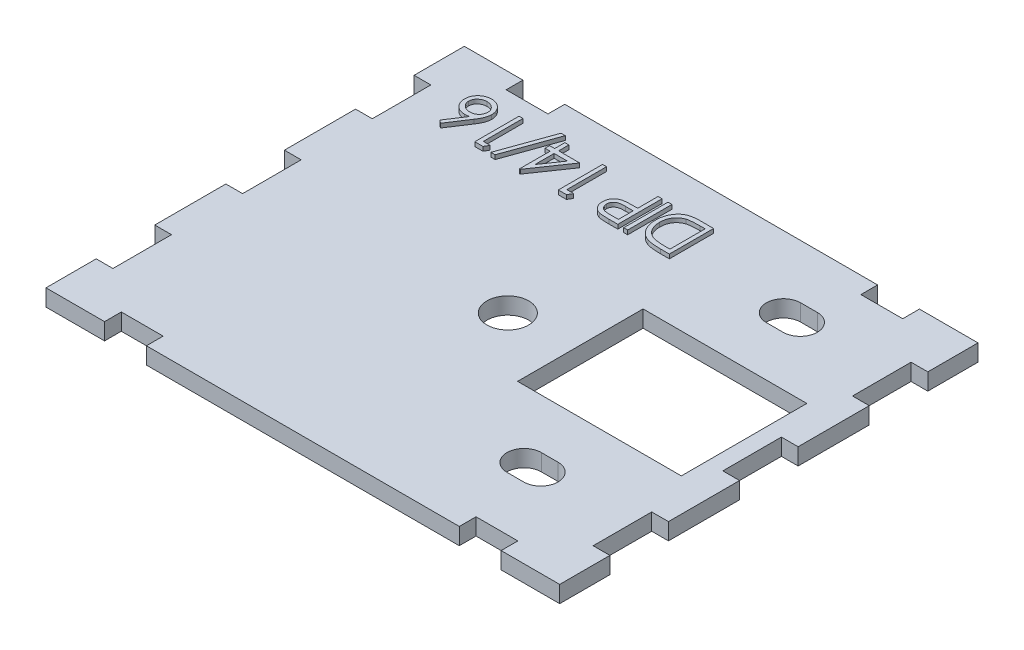
SolidWorks part; units mm, degrees
ref_plane "Front Plane" through (0, 0, 0) normal (0, 0, 1) x (1, 0, 0)
ref_plane "Top Plane" through (0, 0, 0) normal (0, 1, 0) x (1, 0, 0)
ref_plane "Right Plane" through (0, 0, 0) normal (1, 0, 0) x (0, 0, -1)
sketch "Sketch2" plane through (0, 0, 0) normal (0, 1, 0) x (1, 0, 0)
  line L1 (-50, 25) -> (50, 25)
  line L2 (-50, 25) -> (-50, -25)
  line L3 (-50, -25) -> (50, -25)
  line L4 (50, 25) -> (50, -25)
  line L5 (-50, 25) -> (50, -25) construction
  line L6 (-50, -25) -> (50, 25) construction
  point P0 (0, 0)
  dimension "D1" = 100
  dimension "D2" = 50
extrude "Boss-Extrude1" add sketch "Sketch2" along normal blind 2
sketch "Sketch12" plane through (0, 2, 0) normal (0, 1, 0) x (1, 0, 0)
  line L0 (-50, -25) -> (50, -25) construction
  line L1 (-40.2, -25) -> (-50, -25)
  line L2 (-40.2, -25) -> (-40.2, 25)
  line L3 (-40.2, 25) -> (-50, 25)
  line L4 (-50, -25) -> (-50, 25)
  line L5 (-50, -25) -> (50, -25) construction
  line L6 (41.2, -25) -> (50, -25)
  line L7 (41.2, -25) -> (41.2, 25)
  line L8 (41.2, 25) -> (50, 25)
  line L9 (50, -25) -> (50, 25)
extrude "Cut-Extrude8" cut sketch "Sketch12" against normal blind 6
sketch "Sketch13" plane through (0, 2, 0) normal (0, 1, 0) x (1, 0, 0)
  line L1 (-28.2, 19) -> (-30.2, 19)
  line L2 (-28.2, 19) -> (-28.2, 12)
  line L3 (-28.2, 12) -> (-30.2, 12)
  line L4 (-30.2, 19) -> (-30.2, 12)
  line L5 (-28.2, 3.5) -> (-30.2, 3.5)
  line L6 (-28.2, 3.5) -> (-28.2, -3.5)
  line L7 (-28.2, -3.5) -> (-30.2, -3.5)
  line L8 (-30.2, 3.5) -> (-30.2, -3.5)
  line L9 (-28.2, -12) -> (-30.2, -12)
  line L10 (-28.2, -12) -> (-28.2, -19)
  line L11 (-28.2, -19) -> (-30.2, -19)
  line L12 (-30.2, -12) -> (-30.2, -19)
  line L13 (29.2, 19) -> (31.2, 19)
  line L14 (29.2, 19) -> (29.2, 12)
  line L15 (29.2, 12) -> (31.2, 12)
  line L16 (31.2, 19) -> (31.2, 12)
  line L17 (29.2, 3.5) -> (31.2, 3.5)
  line L18 (29.2, 3.5) -> (29.2, -3.5)
  line L19 (29.2, -3.5) -> (31.2, -3.5)
  line L20 (31.2, 3.5) -> (31.2, -3.5)
  line L21 (29.2, -12) -> (31.2, -12)
  line L22 (29.2, -12) -> (29.2, -19)
  line L23 (29.2, -19) -> (31.2, -19)
  line L24 (31.2, -12) -> (31.2, -19)
  line L25 (-40.2, -25) -> (41.2, -25) construction
  line L26 (-23.2, 25) -> (-18.2, 25)
  line L27 (41.2, 25) -> (-40.2, 25) construction
  line L28 (-40.2, -25) -> (41.2, -25) construction
  line L29 (41.2, 25) -> (-40.2, 25) construction
  line L30 (-40.2, -25) -> (41.2, -25) construction
  line L31 (41.2, 25) -> (31.2, 25)
  line L32 (41.2, 25) -> (41.2, -25)
  line L33 (41.2, -25) -> (31.2, -25)
  line L34 (31.2, 25) -> (31.2, -25)
  line L35 (41.2, 25) -> (-40.2, 25) construction
  line L36 (-40.2, -25) -> (-30.2, -25)
  line L37 (-40.2, -25) -> (-40.2, 25)
  line L38 (-40.2, 25) -> (-30.2, 25)
  line L39 (-30.2, -25) -> (-30.2, 25)
  line L40 (-23.2, 25) -> (-23.2, 23)
  line L41 (-23.2, 23) -> (-18.2, 23)
  line L42 (-18.2, 25) -> (-18.2, 23)
  line L43 (-23.2, -25) -> (-18.2, -25)
  line L44 (-23.2, -25) -> (-23.2, -23)
  line L45 (-23.2, -23) -> (-18.2, -23)
  line L46 (-18.2, -25) -> (-18.2, -23)
  line L47 (24.2, -25) -> (19.2, -25)
  line L48 (24.2, -25) -> (24.2, -23)
  line L49 (24.2, -23) -> (19.2, -23)
  line L50 (19.2, -25) -> (19.2, -23)
  line L51 (24.2, 25) -> (19.2, 25)
  line L52 (24.2, 25) -> (24.2, 23)
  line L53 (24.2, 23) -> (19.2, 23)
  line L54 (19.2, 25) -> (19.2, 23)
  point P24 (29.2, 0)
  point P30 (30.2, 3.5)
  line M32 (41.2, -25) -> (41.2, 25)
  line M41 (41.2, 25) -> (-40.2, 25)
  line M42 (-40.2, 25) -> (-40.2, -25)
  line M47 (-40.2, -25) -> (41.2, -25)
  dimension "D1" = 2
  dimension "D2" = 2
  dimension "D3" = 2
  dimension "D4" = 2
  dimension "D5" = 2
  dimension "D6" = 2
  dimension "D7" = 57.4
  dimension "D8" = 57.4
  dimension "D9" = 57.4
  dimension "D10" = 7
  dimension "D11" = 7
  dimension "D12" = 7
  dimension "D13" = 7
  dimension "D14" = 7
  dimension "D15" = 7
  dimension "D16" = 5
  dimension "D17" = 2
  dimension "D18" = 5
  dimension "D19" = 6
  dimension "D20" = 8.5
  dimension "D21" = 8.5
  dimension "D22" = 6
  dimension "D23" = 6
  dimension "D24" = 8.5
  dimension "D25" = 8.5
  dimension "D26" = 6
  dimension "D27" = 5
  dimension "D28" = 5
  dimension "D29" = 2
  dimension "D30" = 2
  dimension "D31" = 5
  dimension "D32" = 5
  dimension "D33" = 5
  dimension "D34" = 5
  dimension "D35" = 2
extrude "Cut-Extrude10" cut sketch "Sketch13" against normal blind 6 contours L5 L8 L7 L6 | L39 L12 L8 L4 M47 M41 M42 | L1 L4 L3 L2 | L50 L48 L49 M47 | L24 L21 L22 L23 | L20 L17 L18 L19 | L16 L13 L14 L15 | L54 L53 L52 M41 | L9 L12 L11 L10 | L34 L16 L20 L24 M41 M47 M32 | L26 L42 L41 L40 | L45 L46 L43 L44
sketch "Sketch15" plane through (0, 0, 0) normal (0, -1, 0) x (1, 0, 0)
  line L0 (24.2, 23) -> (19.2, 23) construction
  line L1 (31.2, -12) -> (31.2, -3.5) construction
  line L16 (20.7242, -7.5) -> (20.7242, -8.5)
  line L17 (20.7242, -7.5) -> (25.936, -7.5)
  line L18 (25.936, -7.5) -> (25.936, 5.5)
  line L19 (25.936, 5.5) -> (8.9693, 5.5)
  line L20 (8.9693, 5.5) -> (8.9693, -7.5)
  line L21 (8.9693, -7.5) -> (14.1811, -7.5)
  line L22 (14.1811, -7.5) -> (14.1811, -8.5)
  line L23 (14.1811, -8.5) -> (7.6661, -8.5)
  line L24 (7.6661, -8.5) -> (7.6661, 6.5)
  line L25 (7.6661, 6.5) -> (27.2392, 6.5)
  line L26 (27.2392, 6.5) -> (27.2392, -8.5)
  line L27 (27.2392, -8.5) -> (20.7242, -8.5)
  line L28 (20.7242, -8.5) -> (14.1811, -8.5)
  line L29 (14.1811, -7.5) -> (20.7242, -7.5)
  dimension "D1" = 13
  dimension "D4" = 16.5
  dimension "D5" = 6.5431
  dimension "D6" = 90
  dimension "D7" = 3.9608
  dimension "D8" = 90
  dimension "D9" = 1.3032
  dimension "D24" = 5.2118
  dimension "D25" = 5.2118
  dimension "D26" = 6.515
  dimension "D27" = 6.515
  dimension "D28" = 1
  dimension "D31" = 90
  dimension "D32" = 90
  dimension "D34" = 1
extrude "Cut-Extrude13" cut sketch "Sketch15" against normal blind 10 contours L21 L29 L17 L18 L19 L20 | L27 L26 L25 L24 L23 L22 L21 L20 L19 L18 L17 L16 | L29 L22 L28 L16
sketch "Sketch16" plane through (0, 0, 0) normal (0, -1, 0) x (-1, 0, 0)
  circle A0 centre (0, 0) radius 2.5
  dimension "D1" = 5
extrude "Cut-Extrude14" cut sketch "Sketch16" against normal blind 10 contours A0
sketch "Sketch17" plane through (0, 0, 0) normal (0, -1, 0) x (-1, 0, 0)
  line L0 (-16.4527, 18.55) -> (-18.4527, 18.55)
  line L1 (-16.4527, 14.45) -> (-18.4527, 14.45)
  line L2 (-27.2392, 8.5) -> (-7.6661, 8.5) construction
  line L3 (-16.4527, -12.45) -> (-18.4527, -12.45)
  line L4 (-7.6661, -6.5) -> (-27.2392, -6.5) construction
  line L5 (-18.4527, -16.55) -> (-16.4527, -16.55)
  circle A0 centre (-17.4527, -14.5) radius 2.05
  circle A1 centre (-17.4527, 16.5) radius 2.05
  circle A2 centre (-16.4527, 16.5) radius 2.05
  circle A3 centre (-18.4527, 16.5) radius 2.05
  circle A4 centre (-18.4527, -14.5) radius 2.05
  circle A5 centre (-16.4527, -14.5) radius 2.05
  dimension "D1" = 4.1
  dimension "D2" = 4.1
  dimension "D9" = 1
  dimension "D10" = 0
  dimension "D12" = 0
  dimension "D15" = 0
  dimension "D16" = 0
  dimension "D3" = 8
  dimension "D4" = 9.7866
  dimension "D5" = 9.7866
  dimension "D6" = 9.7866
  dimension "D7" = 9.7866
  dimension "D8" = 8
  dimension "D11" = 1
  dimension "D13" = 1
  dimension "D14" = 1
extrude "Cut-Extrude15" cut sketch "Sketch17" against normal blind 3.5 contours A4 A0 | A5 A4 A0 | A4 A5 | A0 A5 A4 | A5 A0 | A5 L3 A0 | A5 A0 A4 | A4 A0 L3 | A5 A0 L5 | A5 A4 A0 | A4 L5 A0 | A2 A3 | A1 A3 A2 | A3 A1 | A3 A2 A1 | A3 A1 A2 | A3 A2 A1 | A2 A1 | A2 A1 L1 | A3 L1 A1 | A3 A1 L0 | A2 L0 A1
sketch "Sketch22" plane through (0, 2, 0) normal (0, 1, 0) x (1, 0, 0)
  line L0 (-24.5837, 20.5398) -> (4.8961, 20.5398) construction
  text T0 "DIP 14/16" font "Century Gothic" height in points 20
extrude "Boss-Extrude4" add sketch "Sketch22" along normal blind 0.5
